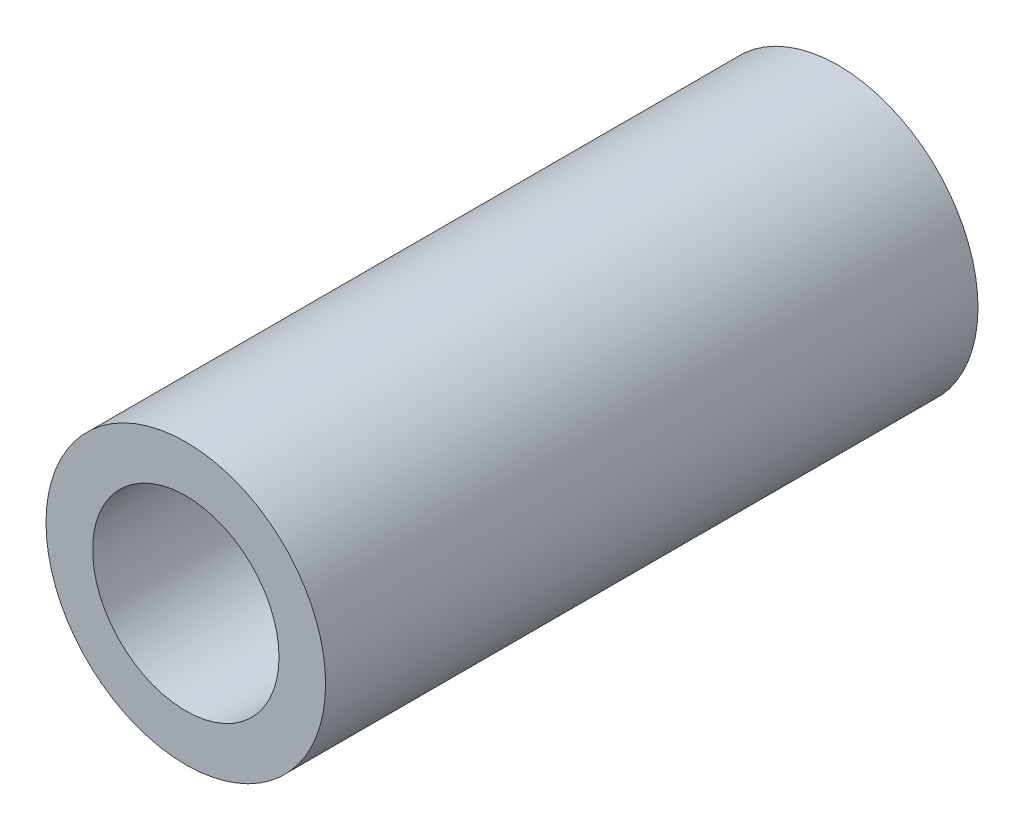
SolidWorks part; units mm, degrees
ref_plane "Front" through (0, 0, 0) normal (0, 0, 1) x (1, 0, 0)
ref_plane "Top" through (0, 0, 0) normal (0, 1, 0) x (1, 0, 0)
ref_plane "Right" through (0, 0, 0) normal (1, 0, 0) x (0, 0, -1)
sketch "Esquisse1" plane through (0, 0, 0) normal (0, 0, 1) x (1, 0, 0)
  circle A0 centre (0, 0) radius 3
  dimension "D1" = 6
extrude "Extru.-Mince1" add sketch "Esquisse1" along normal blind 14 thin thin type one direction reverse wall 1
